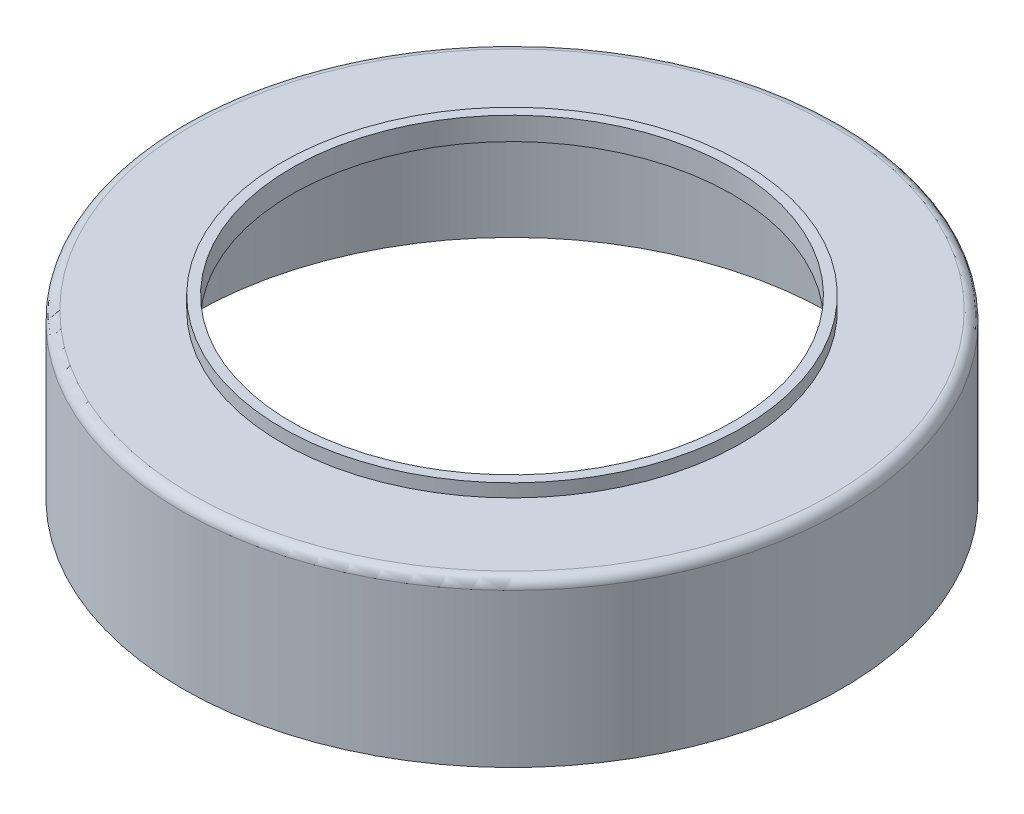
SolidWorks part; units mm, degrees
ref_plane "Front Plane" through (0, 0, 0) normal (0, 0, 1) x (1, 0, 0)
ref_plane "Top Plane" through (0, 0, 0) normal (0, 1, 0) x (1, 0, 0)
ref_plane "Right Plane" through (0, 0, 0) normal (1, 0, 0) x (0, 0, -1)
sketch "Sketch3" plane through (0, 0, 0) normal (0, 1, 0) x (1, 0, 0)
  line L0 (0, 0) -> (-500, 0) construction
  line L1 (0, 0) -> (500, 0) construction
  line L2 (0, 0) -> (0, -500) construction
  line L3 (0, 0) -> (0, 500) construction
  circle A0 centre (0, 0) radius 440 construction
  circle A1 centre (0, 0) radius 500
  circle A2 centre (0, 0) radius 465 construction
  point P8 (-465, 0)
  point P9 (0, -465)
  point P10 (465, 0)
  point P11 (-108.0168, -34.8662)
  dimension "D1" = 880
  dimension "D2" = 1000
  dimension "D5" = 930
  dimension "D3" = 90
  dimension "D4" = 90
ref_plane "Plane1" through (0, 165, 0) normal (0, 1, 0) x (1, 0, 0)
sketch "Sketch4" plane through (0, 165, 0) normal (0, 1, 0) x (1, 0, 0)
  circle A0 centre (0, 0) radius 337.5
  dimension "D1" = 675
ref_plane "Plane2" through (0, 165, 0) normal (0, 1, 0) x (1, 0, 0)
sketch "Sketch5" plane through (0, 165, 0) normal (0, 1, 0) x (1, 0, 0)
  circle A0 centre (0, 0) radius 500
  circle A1 centre (0, 0) radius 500 construction
  point P3 (0, 0)
  point P4 (0, 0)
sketch "Sketch6" plane through (0, 0, 0) normal (0, 0, 1) x (1, 0, 0)
  line L1 (337.5, 165) -> (337.5, 200)
  line L2 (337.5, 200) -> (352.5, 200)
  line L4 (337.5, 165) -> (-337.5, 165) construction
  line L5 (352.5, 200) -> (352.5, 180)
  line L8 (352.5, 180) -> (490, 180)
  line L9 (505, 165) -> (505, 0)
  line L11 (0, 0) -> (0, 165) construction
  line L12 (337.5, 165) -> (490, 165)
  line L13 (490, 165) -> (490, 0)
  line L14 (0, 0) -> (500, 0) construction
  line L15 (490, 0) -> (490, -70)
  line L16 (490, -70) -> (505, -70)
  line L17 (505, -70) -> (505, 0)
  arc A0 (490, 180) -> (505, 165) centre (490, 165) cw
  dimension "D3" = 490
  dimension "D1" = 70
  dimension "D2" = 15
  dimension "D4" = 20
  dimension "D5" = 15
ref_plane "Plane3" through (0, 205, 0) normal (0, 1, 0) x (1, 0, 0)
sketch "Sketch7" plane through (0, 205, 0) normal (0, 1, 0) x (1, 0, 0)
  circle A0 centre (0, 0) radius 337.5 construction
  circle A1 centre (0, 0) radius 337.5
ref_plane "Plane4" through (0, -80, 0) normal (0, 1, 0) x (1, 0, 0)
sketch "Sketch8" plane through (0, -80, 0) normal (0, 1, 0) x (1, 0, 0)
  circle A0 centre (0, 0) radius 500 construction
  circle A1 centre (0, 0) radius 500
revolve "Revolve1" add sketch "Sketch6" angle 360 about L11
ref_plane "Plane5" through (0, -40, 0) normal (0, 1, 0) x (1, 0, 0)
sketch "Sketch9" plane through (0, -40, 0) normal (0, 1, 0) x (1, 0, 0)
  circle A1 centre (0, 0) radius 500
  circle A2 centre (0, 0) radius 500
  dimension "D1" = 0
